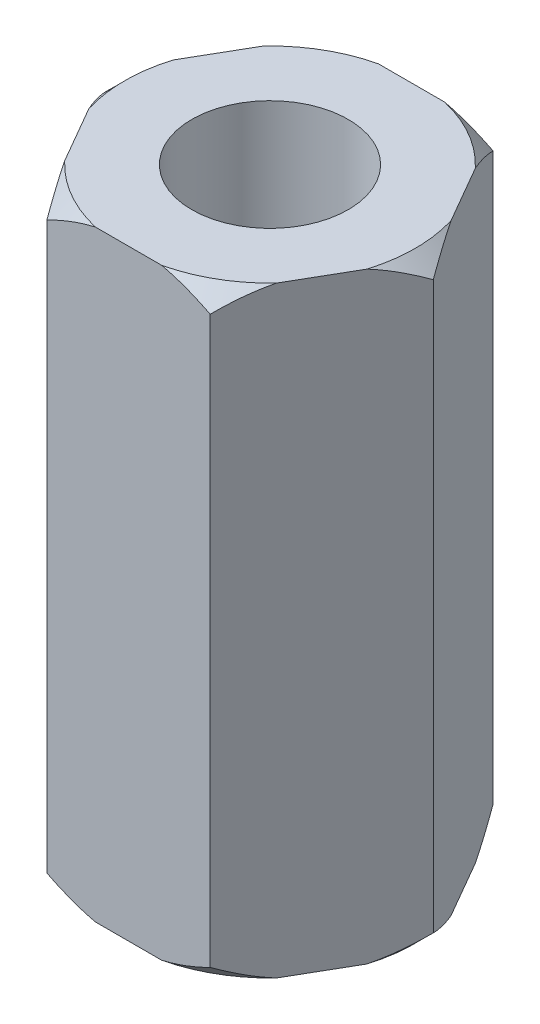
SolidWorks part; units mm, degrees
material "Brass"
ref_plane "Front" through (0, 0, 0) normal (0, 0, 1) x (1, 0, 0)
ref_plane "Top" through (0, 0, 0) normal (0, 1, 0) x (1, 0, 0)
ref_plane "Right" through (0, 0, 0) normal (1, 0, 0) x (0, 0, -1)
sketch "Sketch1" plane through (0, 0, 0) normal (0, 1, 0) x (1, 0, 0)
  line L1 (-2.7135, 0) -> (-1.3568, -2.35)
  line L2 (-1.3568, -2.35) -> (1.3568, -2.35)
  line L3 (1.3568, -2.35) -> (2.7135, 0)
  line L4 (2.7135, 0) -> (1.3568, 2.35)
  line L5 (1.3568, 2.35) -> (-1.3568, 2.35)
  line L6 (-1.3568, 2.35) -> (-2.7135, 0)
  circle A0 centre (0, 0) radius 1.3
  circle A1 centre (0, 0) radius 2.35 construction
  dimension "D2" = 2.6
  dimension "D1" = 4.7
extrude "Boss-Extrude1" add sketch "Sketch1" along normal blind 10
cosmetic thread "Cosmetic Thread2" parameters "D2"=3.5
sketch "Sketch6" plane through (0, 0, 0) normal (0, 0, 1) x (1, 0, 0)
  line L0 (0, 0) -> (0, 8.532) construction
  line L1 (-2.7135, 5) -> (-7.8723, 5) construction
  line L2 (-2.7135, 10) -> (-2.7135, 0) construction
  line L3 (-2.7135, 10) -> (-2.7135, 9.7)
  line L4 (-2.7135, 9.7) -> (-2.4135, 10)
  line L5 (-2.4135, 10) -> (-2.7135, 10)
  line L6 (-2.4135, 0) -> (-2.7135, 0)
  line L7 (-2.7135, 0.3) -> (-2.4135, 0)
  line L8 (-2.7135, 0) -> (-2.7135, 0.3)
  dimension "D1" = 45
  dimension "D2" = 0.3
revolve "Cut-Revolve1" cut sketch "Sketch6" angle 360 about L0
